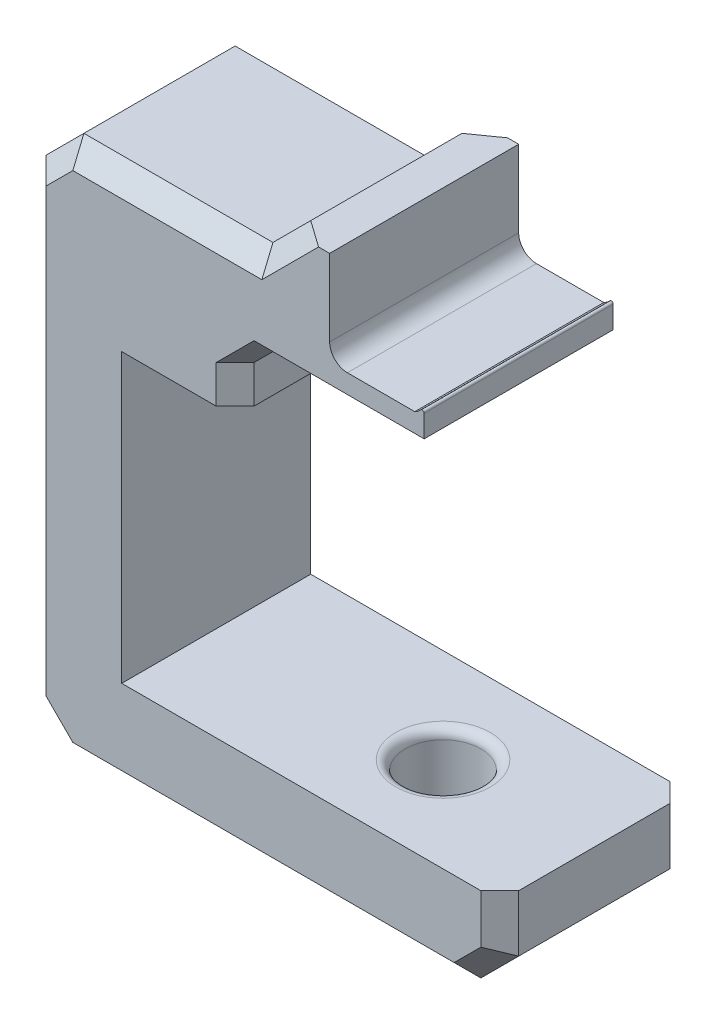
SolidWorks part; units mm, degrees
ref_plane "Plano frontal" through (0, 0, 0) normal (0, 0, 1) x (1, 0, 0)
ref_plane "Plano superior" through (0, 0, 0) normal (0, 1, 0) x (1, 0, 0)
ref_plane "Plano direito" through (0, 0, 0) normal (1, 0, 0) x (0, 0, -1)
sketch "Esboço1" plane through (0, 0, 0) normal (0, 0, 1) x (1, 0, 0)
  line L0 (11, 14.25) -> (1, 14.25)
  line L1 (1, 11.25) -> (-5, 11.25)
  line L3 (-5, -3.95) -> (15, -3.95)
  line L4 (15, -3.95) -> (15, -8.95)
  line L5 (15, -8.95) -> (-10, -8.95)
  line L6 (-10, -8.95) -> (-10, 19.25)
  line L7 (1, 14.25) -> (1, 11.25)
  line L9 (-5, 11.25) -> (-5, -3.95)
  line L10 (11, 14.25) -> (11, 16.25)
  line L11 (10.5044, 16.25) -> (6, 16.25)
  line L12 (6, 16.25) -> (6, 19.25)
  line L13 (6, 19.25) -> (-10, 19.25)
  line L14 (11, 16.25) -> (11, 16.4263)
  arc A0 (11, 16.4263) -> (10.8262, 16.4939) centre (10.9, 16.4263) ccw
  arc A1 (10.5044, 16.25) -> (10.8262, 16.4939) centre (10, 17.25) ccw
  dimension "D12" = 0.1
  dimension "D2" = 20
  dimension "D3" = 15.2
  dimension "D4" = 6
  dimension "D5" = 3
  dimension "D6" = 5
  dimension "D7" = 2
  dimension "D8" = 5
  dimension "D10" = 16
  dimension "D11" = 5
  dimension "D13" = 0.1763
  dimension "D14" = 0.4956
extrude "Ressalto-extrusão1" add sketch "Esboço1" along normal blind 10
sketch "Esboço3" plane through (0, -8.95, 0) normal (0, -1, 0) x (1, 0, 0)
  line L0 (15, 5) -> (7, 5) construction
  line L1 (15, 10) -> (15, 0) construction
  circle A0 centre (7, 5) radius 2
  dimension "D1" = 4
  dimension "D2" = 8
extrude "Corte-extrusão1" cut sketch "Esboço3" against normal blind 15
chamfer "Chanfro1" distance 1.6 angle 45 1 edges at (7, -8.95, 3)
fillet "Filete1" radius 0.5 1 edges at (7, -3.95, 3)
fillet "Filete2" radius 0.94 1 edges at (6, 16.25, 5)
sketch "Esboço5" plane through (0, 0, 10) normal (0, 0, 1) x (1, 0, 0)
  line L0 (6, 19.25) -> (6, 21.25)
  line L1 (6, 21.25) -> (4, 21.25)
  line L2 (4, 21.25) -> (2, 19.25)
  line L3 (6, 19.25) -> (-10, 19.25) construction
  line L4 (2, 19.25) -> (6, 19.25)
  dimension "D1" = 135
  dimension "D2" = 2
  dimension "D3" = 2
extrude "Ressalto-extrusão3" add sketch "Esboço5" against normal up to surface (10 mm away) up to face at (4.274, 9.744, 0)
chamfer "Chanfro5" distance 2 angle 45 3 edges at (15, -8.95, 5) (-10, -8.95, 5) (-10, 19.25, 5)
chamfer "Chanfro4" distance 1 angle 45 22 edges at (6, 14.25, 0) (6, 14.25, 10) (11, 14.25, 5) (3, 20.25, 0) (3, 20.25, 10) (-3, 19.25, 0) (-9, 18.25, 0) (-10, 5.15, 0) (-9, -7.95, 0) (2.5, -8.95, 0) (14, -7.95, 0) (15, -5.45, 0) (-3, 19.25, 10) (-9, 18.25, 10) (-10, 5.15, 10) (-9, -7.95, 10) (2.5, -8.95, 10) (14, -7.95, 10) (15, -5.45, 10) (1, 12.75, 0) (1, 12.75, 10) (1, 14.25, 5)
